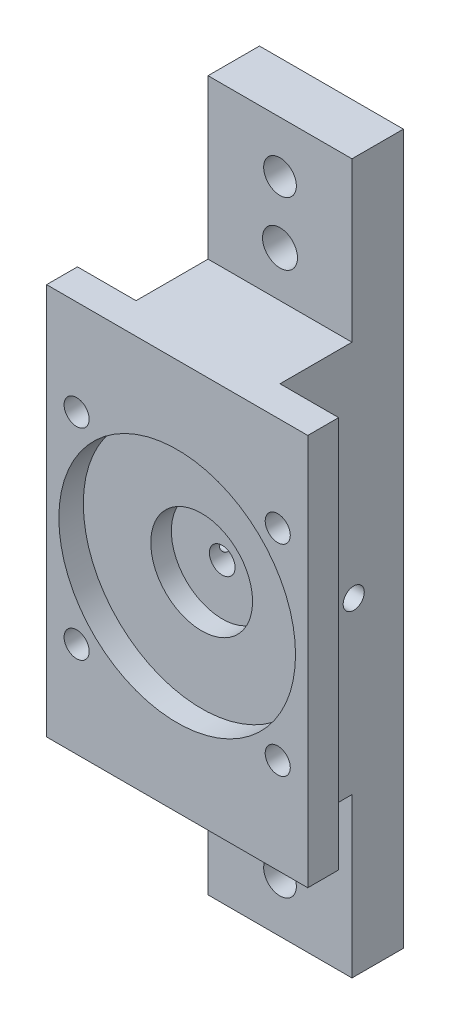
SolidWorks part; units mm, degrees
material "6061-T6 (SS)"
ref_plane "Front Plane" through (0, 0, 0) normal (0, 0, 1) x (1, 0, 0)
ref_plane "Top Plane" through (0, 0, 0) normal (0, 1, 0) x (1, 0, 0)
ref_plane "Right Plane" through (0, 0, 0) normal (1, 0, 0) x (0, 0, -1)
sketch "Sketch1" plane through (0, 0, 0) normal (0, 0, 1) x (1, 0, 0)
  line L1 (0, 0) -> (25.4, 0)
  line L2 (0, 0) -> (0, 38.1)
  line L3 (0, 38.1) -> (25.4, 38.1)
  line L4 (25.4, 0) -> (25.4, 38.1)
  dimension "D1" = 38.1
  dimension "D2" = 25.4
extrude "Boss-Extrude1" add sketch "Sketch1" along normal blind 15
sketch "Sketch2" plane through (0, 0, 15) normal (0, 0, 1) x (1, 0, 0)
  line L0 (25.4, 0) -> (25.4, 38.1) construction
  line L1 (0, 0) -> (25.4, 0) construction
  circle A0 centre (12.7, 19.05) radius 11.51
  dimension "D1" = 23.02
  dimension "D2" = 12.7
  dimension "D3" = 19.05
extrude "Cut-Extrude1" cut sketch "Sketch2" against normal blind 2.38
sketch "Sketch3" plane through (0, 0, 12.62) normal (0, 0, 1) x (1, 0, 0)
  circle A0 centre (12.7, 19.05) radius 4.95
  dimension "D1" = 9.9
extrude "Cut-Extrude2" cut sketch "Sketch3" against normal blind 2
sketch "Sketch4" plane through (0, 0, 10.62) normal (0, 0, 1) x (1, 0, 0)
  circle A0 centre (12.7, 19.05) radius 0.625
  dimension "D1" = 1.25
extrude "Cut-Extrude3" cut sketch "Sketch4" against normal through all
sketch "Sketch5" plane through (0, 0, 15) normal (0, 0, 1) x (1, 0, 0)
  circle A0 centre (2.92, 28.83) radius 1.22
  circle A1 centre (22.48, 28.83) radius 1.22
  circle A2 centre (22.48, 9.27) radius 1.22
  circle A3 centre (2.92, 9.27) radius 1.22
  circle A4 centre (12.7, 19.05) radius 0.625 construction
  dimension "D1" = 2.44
  dimension "D2" = 2.44
  dimension "D3" = 2.44
  dimension "D4" = 2.44
  dimension "D5" = 9.78
  dimension "D6" = 9.78
  dimension "D7" = 9.78
  dimension "D8" = 9.78
  dimension "D9" = 9.78
  dimension "D10" = 9.78
  dimension "D11" = 9.78
  dimension "D12" = 9.78
extrude "Cut-Extrude4" cut sketch "Sketch5" against normal through all
sketch "Sketch7" plane through (0, 38.1, 0) normal (0, 1, 0) x (1, 0, 0)
  line L1 (0, 0) -> (5.7, 0)
  line L2 (0, 0) -> (0, -12)
  line L3 (0, -12) -> (5.7, -12)
  line L4 (5.7, 0) -> (5.7, -12)
  line L5 (25.4, 0) -> (19.7, 0)
  line L6 (25.4, 0) -> (25.4, -12)
  line L7 (25.4, -12) -> (19.7, -12)
  line L8 (19.7, 0) -> (19.7, -12)
  line L9 (25.4, -15) -> (0, -15) construction
  line L10 (25.4, 0) -> (0, 0) construction
  point P14 (12.7, 0)
  dimension "D1" = 14
  dimension "D2" = 7
  dimension "D3" = 3
  dimension "D4" = 3
extrude "Cut-Extrude5" cut sketch "Sketch7" against normal through all
sketch "Sketch12" plane through (19.7, 0, 0) normal (1, 0, 0) x (0, 0, -1)
  line L1 (0, 38.1) -> (-5, 38.1)
  line L2 (0, 38.1) -> (0, 53.55)
  line L3 (0, 53.55) -> (-5, 53.55)
  line L4 (-5, 38.1) -> (-5, 53.55)
  line L5 (0, 0) -> (-5, 0)
  line L6 (0, 0) -> (0, -15.45)
  line L7 (0, -15.45) -> (-5, -15.45)
  line L8 (-5, 0) -> (-5, -15.45)
  dimension "D1" = 5
  dimension "D2" = 5
  dimension "D3" = 69
  dimension "D4" = 15.45
extrude "Boss-Extrude2" add sketch "Sketch12" against normal up to surface (14 mm away) up to face at (5.7, 19.05, 6)
sketch "Sketch13" plane through (0, 0, 5) normal (0, 0, 1) x (1, 0, 0)
  line L0 (5.7, -15.45) -> (19.7, -15.45) construction
  line L2 (5.7, 53.55) -> (19.7, 53.55) construction
  circle A0 centre (12.7, 48.55) radius 1.59
  circle A1 centre (12.7, 42.55) radius 1.7
  circle A2 centre (12.7, -4.45) radius 1.7
  circle A3 centre (12.7, -10.45) radius 1.59
  point P10 (12.7, -15.45)
  point P11 (12.7, 53.55)
  dimension "D1" = 3.18
  dimension "D2" = 3.4
  dimension "D3" = 5
  dimension "D4" = 11
  dimension "D5" = 0
  dimension "D6" = 0
  dimension "D7" = 3.18
  dimension "D8" = 3.4
  dimension "D9" = 5
  dimension "D10" = 11
  dimension "D11" = 0
  dimension "D12" = 0
extrude "Cut-Extrude8" cut sketch "Sketch13" against normal blind 7.5
sketch "Sketch18" plane through (19.7, 0, 0) normal (1, 0, 0) x (0, 0, -1)
  line L0 (0, -15.45) -> (0, 53.55) construction
  line L1 (-5, -15.45) -> (0, -15.45) construction
  circle A0 centre (-4.83, 16.46) radius 1.025
  dimension "D1" = 2.05
  dimension "D2" = 4.83
  dimension "D3" = 31.91
hole_wizard "Tap Drill for M2.5x0.45 Tap1" positions "Sketch19" profile "Sketch20" hole size "M2.5x0.45" standard "ANSI Metric"
sketch "Sketch19" plane through (19.7, 0, 0) normal (1, 0, 0) x (0, 0, -1)
  point P0 (-4.83, 16.46)
sketch "Sketch20" plane through (19.7, 16.46, 4.83) normal (0, 1, 0) x (0, 0, -1)
  line L0 (0, 0) -> (0, 2.7659)
  line L1 (0, 2.7659) -> (1.025, 2.15)
  line L2 (1.025, 2.15) -> (1.025, 0)
  line L5 (1.025, 0) -> (0, 0)
  line L10 (0, 2.7659) -> (-1.025, 2.15) construction
  line L11 (0, -6.35) -> (0, 107.95) construction
  dimension "Hole Dia." = 2.05
  dimension "Hole Depth" = 2.15
  dimension "Drill Angle" = 118
sketch "Sketch21" plane through (0, 0, 0) normal (0, 0, -1) x (-1, 0, 0)
  line L1 (-15.2, 12.55) -> (-10.2, 12.55)
  line L2 (-15.2, 12.55) -> (-15.2, 25.55)
  line L3 (-15.2, 25.55) -> (-10.2, 25.55)
  line L4 (-10.2, 12.55) -> (-10.2, 25.55)
  line L5 (-15.2, 12.55) -> (-10.2, 25.55) construction
  line L6 (-15.2, 25.55) -> (-10.2, 12.55) construction
  point P0 (-12.7, 19.05)
  dimension "D1" = 5
  dimension "D2" = 13
extrude "Cut-Extrude10" cut sketch "Sketch21" against normal blind 0.8
fillet "Fillet1" radius 0.79 4 edges at (10.2, 12.55, 0.4) (15.2, 12.55, 0.4) (15.2, 25.55, 0.4) (10.2, 25.55, 0.4)
sketch "Sketch22" plane through (5.7, 0, 0) normal (-1, 0, 0) x (0, 0, 1)
  line L0 (12, 0) -> (12, 38.1) construction
  line L1 (4, 24.05) -> (12, 24.05)
  line L2 (4, 24.05) -> (4, 14.05)
  line L3 (4, 14.05) -> (12, 14.05)
  line L4 (12, 24.05) -> (12, 14.05)
  line L5 (0, -15.45) -> (0, 53.55) construction
  line L6 (15, 38.1) -> (15, 0) construction
  point P6 (4, 19.05)
  point P9 (0, 19.05)
  dimension "D1" = 0
  dimension "D2" = 10
  dimension "D3" = 11
extrude "Boss-Extrude3" add sketch "Sketch22" along normal up to surface (5.7 mm away) up to face at (0, 19.05, 13.5)
sketch "Sketch23" plane through (0, 0, 0) normal (-1, 0, 0) x (0, 0, 1)
  line L0 (15, 38.1) -> (15, 0) construction
  line L2 (0, -15.45) -> (0, 53.55) construction
  circle A0 centre (9, 19.05) radius 2.02
  point P6 (0, 19.05)
  dimension "D1" = 4.04
  dimension "D2" = 6
  dimension "D3" = 0
extrude "Cut-Extrude11" cut sketch "Sketch23" against normal blind 5.5
hole_wizard "Tap Drill for #10-32 Tap1" positions "Sketch24" profile "Sketch25" hole size "#10-32" standard "ANSI Inch"
sketch "Sketch24" plane through (0, 0, 0) normal (-1, 0, 0) x (0, 0, 1)
  point P0 (9, 19.05)
sketch "Sketch25" plane through (0, 19.05, 9) normal (0, 1, 0) x (0, 0, 1)
  line L0 (0, 0) -> (0, 6.7133)
  line L1 (0, 6.7133) -> (2.0193, 5.5)
  line L2 (2.0193, 5.5) -> (2.0193, 0)
  line L5 (2.0193, 0) -> (0, 0)
  line L10 (0, 6.7133) -> (-2.0193, 5.5) construction
  line L11 (0, -6.35) -> (0, 107.95) construction
  dimension "Hole Dia." = 4.0386
  dimension "Hole Depth" = 5.5
  dimension "Drill Angle" = 118
sketch "Sketch26" plane through (0, 0, 0) normal (-1, 0, 0) x (0, 0, 1)
  circle A0 centre (9, 19.05) radius 0.625
  dimension "D1" = 1.25
extrude "Cut-Extrude12" cut sketch "Sketch26" against normal blind 12.7
sketch "Sketch27" plane through (0, 0, 10.62) normal (0, 0, 1) x (1, 0, 0)
  circle A0 centre (12.7, 19.05) radius 1.25
  dimension "D1" = 2.5
extrude "Cut-Extrude13" cut sketch "Sketch27" against normal blind 8.22
